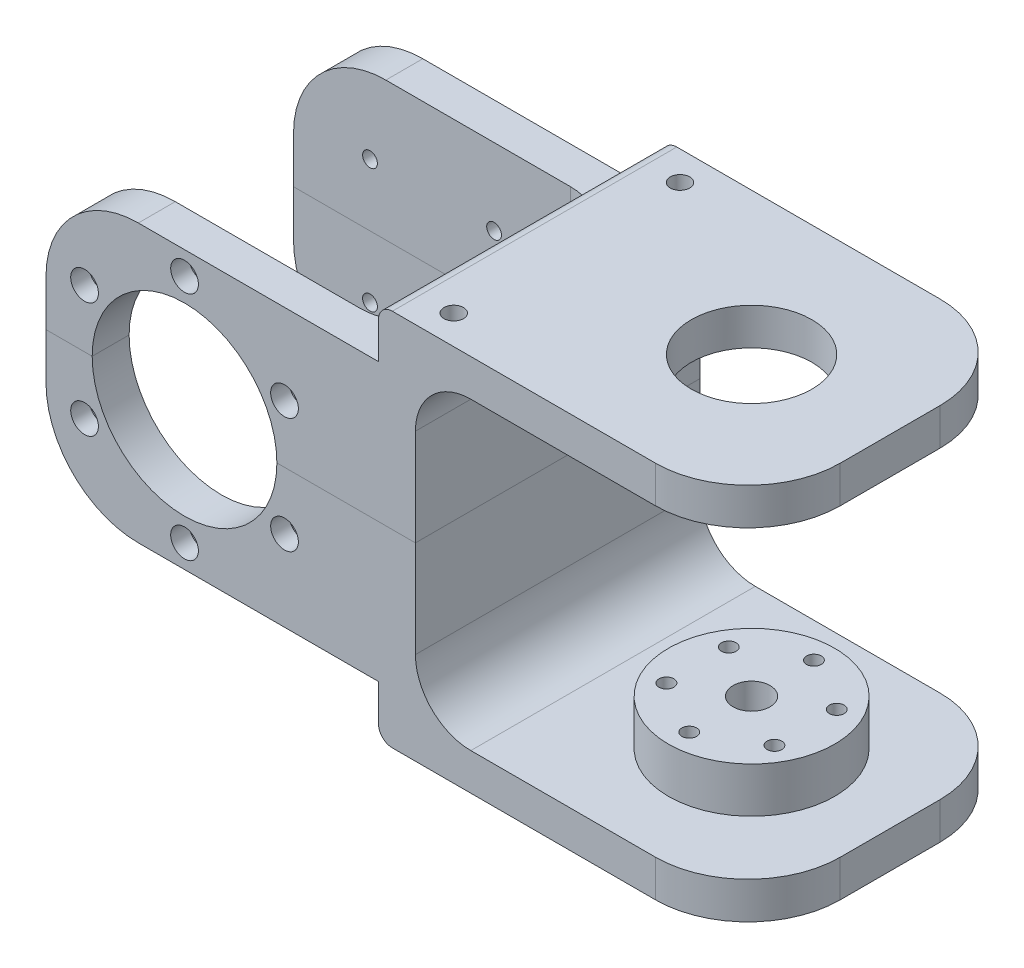
SolidWorks part; units mm, degrees
ref_plane "前视基准面" through (0, 0, 0) normal (0, 0, 1) x (1, 0, 0)
ref_plane "上视基准面" through (0, 0, 0) normal (0, 1, 0) x (1, 0, 0)
ref_plane "右视基准面" through (0, 0, 0) normal (1, 0, 0) x (0, 0, -1)
other "Configuration Table"
sketch "草图1" plane through (0, 0, 0) normal (0, 1, 0) x (1, 0, 0)
  line L1 (40, -30.8) -> (-40, -30.8)
  line L2 (40, -30.8) -> (40, 30.8)
  line L3 (40, 30.8) -> (-40, 30.8)
  line L4 (-40, -30.8) -> (-40, 30.8)
  line L5 (40, -30.8) -> (-40, 30.8) construction
  line L6 (40, 30.8) -> (-40, -30.8) construction
  point P0 (0, 0)
  dimension "D1" = 61.6
  dimension "D2" = 80
extrude "凸台-拉伸1" add sketch "草图1" along normal blind 8
sketch "草图2" plane through (0, 8, 0) normal (0, 1, 0) x (1, 0, 0)
  line L0 (-40, 30.8) -> (-40, -30.8) construction
  line L1 (-32, -30.8) -> (-40, -30.8)
  line L2 (-32, -30.8) -> (-32, 30.8)
  line L3 (-32, 30.8) -> (-40, 30.8)
  line L4 (-40, -30.8) -> (-40, 30.8)
  line L5 (-32, -30.8) -> (-40, 30.8) construction
  line L6 (-32, 30.8) -> (-40, -30.8) construction
  line L7 (40, 30.8) -> (-40, 30.8) construction
  line L8 (-40, -30.8) -> (40, -30.8) construction
  point P0 (-36, 0)
  dimension "D1" = 8
extrude "凸台-拉伸2" add sketch "草图2" along normal blind 52.9
sketch "草图10" plane through (0, 60.9, 0) normal (0, 1, 0) x (1, 0, 0)
  line L0 (-40, -30.8) -> (-40, 30.8) construction
  line L1 (-32, -30.8) -> (-40, -30.8)
  line L2 (-32, -30.8) -> (-32, 30.8)
  line L3 (-32, 30.8) -> (-40, 30.8)
  line L4 (-40, -30.8) -> (-40, 30.8)
  line L5 (-32, -30.8) -> (-40, 30.8) construction
  line L6 (-32, 30.8) -> (-40, -30.8) construction
  line L7 (-32, 30.8) -> (-40, 30.8) construction
  line L8 (-32, -30.8) -> (-32, 30.8) construction
  line L9 (-32, -30.8) -> (-40, -30.8) construction
  point P0 (-36, 0)
extrude "凸台-拉伸7" add sketch "草图10" along normal blind 13
sketch "草图11" plane through (0, 73.9, 0) normal (0, 1, 0) x (1, 0, 0)
  line L0 (-40, -30.8) -> (-40, 30.8) construction
  line L1 (40, -30.8) -> (-40, -30.8)
  line L2 (40, -30.8) -> (40, 30.8)
  line L3 (40, 30.8) -> (-40, 30.8)
  line L4 (-40, -30.8) -> (-40, 30.8)
  line L5 (40, -30.8) -> (-40, 30.8) construction
  line L6 (40, 30.8) -> (-40, -30.8) construction
  line L7 (40, -30.8) -> (40, 30.8) construction
  line L8 (40, 30.8) -> (-40, 30.8) construction
  line L9 (40, -30.8) -> (-40, -30.8) construction
  point P0 (0, 0)
extrude "凸台-拉伸8" add sketch "草图11" along normal blind 8
sketch "草图3" plane through (-40, 0, 0) normal (-1, 0, 0) x (0, 0, 1)
  line L1 (-22.8, 10.95) -> (-30.8, 10.95)
  line L2 (-22.8, 10.95) -> (-22.8, 70.95)
  line L3 (-22.8, 70.95) -> (-30.8, 70.95)
  line L4 (-30.8, 10.95) -> (-30.8, 70.95)
  line L5 (-22.8, 10.95) -> (-30.8, 70.95) construction
  line L6 (-22.8, 70.95) -> (-30.8, 10.95) construction
  line L7 (-30.8, 81.9) -> (-30.8, 0) construction
  line L10 (30.8, 10.95) -> (22.8, 10.95)
  line L11 (30.8, 10.95) -> (30.8, 70.95)
  line L12 (30.8, 70.95) -> (22.8, 70.95)
  line L13 (22.8, 10.95) -> (22.8, 70.95)
  line L14 (30.8, 10.95) -> (22.8, 70.95) construction
  line L15 (30.8, 70.95) -> (22.8, 10.95) construction
  line L17 (30.8, 81.9) -> (30.8, 0) construction
  point P0 (-26.8, 40.95)
  point P5 (-30.8, 40.95)
  point P6 (-30.8, 40.95)
  point P9 (30.8, 40.95)
  point P10 (30.8, 40.95)
  point P11 (26.8, 40.95)
  dimension "D1" = 8
  dimension "D2" = 8
  dimension "D3" = 60
  dimension "D4" = 60
extrude "凸台-拉伸3" add sketch "草图3" along normal blind 72
sketch "草图6" plane through (0, 8, 0) normal (0, 1, 0) x (1, 0, 0)
  line L1 (40, 30.8) -> (-40, 30.8) construction
  line L3 (40, -30.8) -> (40, 30.8) construction
  circle A0 centre (10, 0) radius 18
  point P2 (0, 30.8)
  point P3 (40, 0)
  point P6 (10, 30.8)
  dimension "D3" = 36
  dimension "D1" = 10
extrude "凸台-拉伸4" add sketch "草图6" along normal blind 9.8
sketch "草图4" plane through (0, 8, 0) normal (0, 1, 0) x (1, 0, 0)
  line L2 (40, -30.8) -> (40, 30.8) construction
  line L3 (40, 30.8) -> (-40, 30.8) construction
  circle A0 centre (10, 0) radius 13.5 construction
  circle A1 centre (10, 13.5) radius 1.6
  circle A2 centre (21.6913, 6.75) radius 1.6
  circle A3 centre (21.6913, -6.75) radius 1.6
  circle A4 centre (10, -13.5) radius 1.6
  circle A5 centre (-1.6913, -6.75) radius 1.6
  circle A6 centre (-1.6913, 6.75) radius 1.6
  circle A7 centre (10, 0) radius 4
  point P2 (40, 0)
  point P3 (10, 30.8)
  point P9 (0, 30.8)
  point P21 (10, 0)
  dimension "D1" = 27
  dimension "D4" = 3.2
  dimension "D6" = 8
  dimension "D2" = 10
  dimension "D5" = 6
extrude "切除-拉伸1" cut sketch "草图4" against normal through all and the other way up to next
sketch "草图5" plane through (0, 0, -22.8) normal (0, 0, 1) x (1, 0, 0)
  line L0 (-82, 40.95) -> (-82, 70.95) construction
  line L1 (-82, 40.95) -> (-68.565, 54.385) construction
  line L2 (-112, 70.95) -> (-40, 70.95) construction
  line L3 (-112, 10.95) -> (-112, 70.95) construction
  circle A0 centre (-82, 40.95) radius 19 construction
  circle A1 centre (-68.565, 54.385) radius 1.6
  circle A2 centre (-68.565, 27.515) radius 1.6
  circle A3 centre (-95.435, 27.515) radius 1.6
  circle A4 centre (-95.435, 54.385) radius 1.6
  point P2 (-76, 70.95)
  point P3 (-82, 70.95)
  point P8 (-112, 40.95)
  point P17 (-82, 40.95)
  dimension "D3" = 38
  dimension "D4" = 3.2
  dimension "D1" = 6
  dimension "D2" = 45
  dimension "D5" = 4
extrude "切除-拉伸2" cut sketch "草图5" against normal through all
sketch "草图12" plane through (0, 73.9, 0) normal (0, -1, 0) x (-1, 0, 0)
  circle A0 centre (-10, 0) radius 13.05
  dimension "D1" = 26.1
extrude "切除-拉伸3" cut sketch "草图12" against normal up to next
sketch "草图14" plane through (0, 0, 30.8) normal (0, 0, 1) x (1, 0, 0)
  circle A0 centre (-82, 40.95) radius 25 construction
  circle A1 centre (-82, 65.95) radius 1.6
  circle A2 centre (-60.3494, 53.45) radius 1.6
  circle A3 centre (-60.3494, 28.45) radius 1.6
  circle A4 centre (-82, 15.95) radius 1.6
  circle A5 centre (-103.6506, 28.45) radius 1.6
  circle A6 centre (-103.6506, 53.45) radius 1.6
  circle A7 centre (-82, 40.95) radius 20
  point P21 (-82, 40.95)
  dimension "D1" = 50
  dimension "D4" = 3.2
  dimension "D6" = 40
  dimension "D5" = 6
extrude "切除-拉伸5" cut sketch "草图14" against normal up to next
sketch "草图16" plane through (0, 0, -30.8) normal (0, 0, -1) x (-1, 0, 0)
  circle A0 centre (82, 40.95) radius 8.45
  dimension "D1" = 16.9
extrude "凸台-拉伸9" add sketch "草图16" along normal blind 14.8
ref_plane "基准面2" through (0, 0, -43.6) normal (0, 0, -1) x (-1, 0, 0)
fillet "圆角1" radius 12 4 edges at (-40, 40.95, -22.8) (-32, 8, 0) (-32, 73.9, 0) (-40, 40.95, 22.8)
fillet "圆角2" radius 20 8 edges at (40, 4, 30.8) (40, 4, -30.8) (-112, 70.95, -26.8) (-112, 10.95, -26.8) (40, 77.9, -30.8) (40, 77.9, 30.8) (-112, 10.95, 26.8) (-112, 70.95, 26.8)
fillet "圆角3" radius 3 2 edges at (-40, 81.9, 0) (-40, 0, 0)
sketch "草图17" plane through (0, 0, -43.6) normal (0, 0, -1) x (-1, 0, 0)
  circle A1 centre (82, 40.95) radius 8.45
  circle A2 centre (82, 40.95) radius 7.45
  dimension "D1" = 16.9
  dimension "D2" = 14.9
extrude "切除-拉伸6" cut sketch "草图17" against normal blind 1.6
sketch "草图18" plane through (0, 81.9, 0) normal (0, 1, 0) x (1, 0, 0)
  line L0 (-40, 10.8) -> (-40, 30.8) construction
  line L2 (40, -10.8) -> (40, 10.8) construction
  line L3 (-40, 0) -> (40, 0) construction
  line L4 (-40, -30.8) -> (-40, 30.8) construction
  line L5 (-30, 24.5) -> (-30, -24.5) construction
  circle A1 centre (-30, 24.5) radius 2.1
  circle A2 centre (-30, -24.5) radius 2.1
  dimension "D1" = 10
  dimension "D4" = 4.2
  dimension "D2" = 49
extrude "切除-拉伸7" cut sketch "草图18" against normal up to surface (8 mm away) up to face at (10, 73.9, -13.05)
sketch "草图19" plane through (0, 0, -30.8) normal (0, 0, -1) x (-1, 0, 0)
  circle A0 centre (68.565, 27.515) radius 3
  circle A1 centre (68.565, 54.385) radius 3
  circle A2 centre (95.435, 54.385) radius 3
  circle A3 centre (95.435, 27.515) radius 3
  point P12 (82, 40.95)
  dimension "D1" = 6
  dimension "D2" = 4
extrude "切除-拉伸8" cut sketch "草图19" against normal blind 4
sketch "草图20" plane through (0, 0, 30.8) normal (0, 0, 1) x (1, 0, 0)
  line L0 (-82, 40.95) -> (-82, 65.95) construction
  line L1 (-82, 40.95) -> (-60.3494, 53.45) construction
  circle A0 centre (-82, 65.95) radius 3
  circle A1 centre (-60.3494, 53.45) radius 3
  circle A2 centre (-60.3494, 28.45) radius 3
  circle A3 centre (-82, 15.95) radius 3
  circle A4 centre (-103.6506, 28.45) radius 3
  circle A5 centre (-103.6506, 53.45) radius 3
  dimension "D1" = 6
  dimension "D3" = 60
  dimension "D2" = 6
extrude "切除-拉伸9" cut sketch "草图20" against normal blind 4
sketch "草图21" plane through (0, 0, 0) normal (0, -1, 0) x (-1, 0, 0)
  circle A0 centre (-10, -13.5) radius 3
  circle A1 centre (-21.6913, -6.75) radius 3
  circle A2 centre (-21.6913, 6.75) radius 3
  circle A3 centre (-10, 13.5) radius 3
  circle A4 centre (1.6913, 6.75) radius 3
  circle A5 centre (1.6913, -6.75) radius 3
  point P16 (-10, 0)
  dimension "D1" = 6
  dimension "D2" = 6
extrude "切除-拉伸10" cut sketch "草图21" against normal blind 4
sketch "草图22" plane through (0, 0, -30.8) normal (0, 0, -1) x (-1, 0, 0)
  circle A0 centre (82, 40.95) radius 9.5
  dimension "D1" = 19
extrude "凸台-拉伸10" add sketch "草图22" along normal blind 1
ref_plane "基准面3" through (0, 40.95, 0) normal (0, 1, 0) x (1, 0, 0)
split "分割1" trim tools "基准面3" bodies to split 130 resulting bodies 131 132
